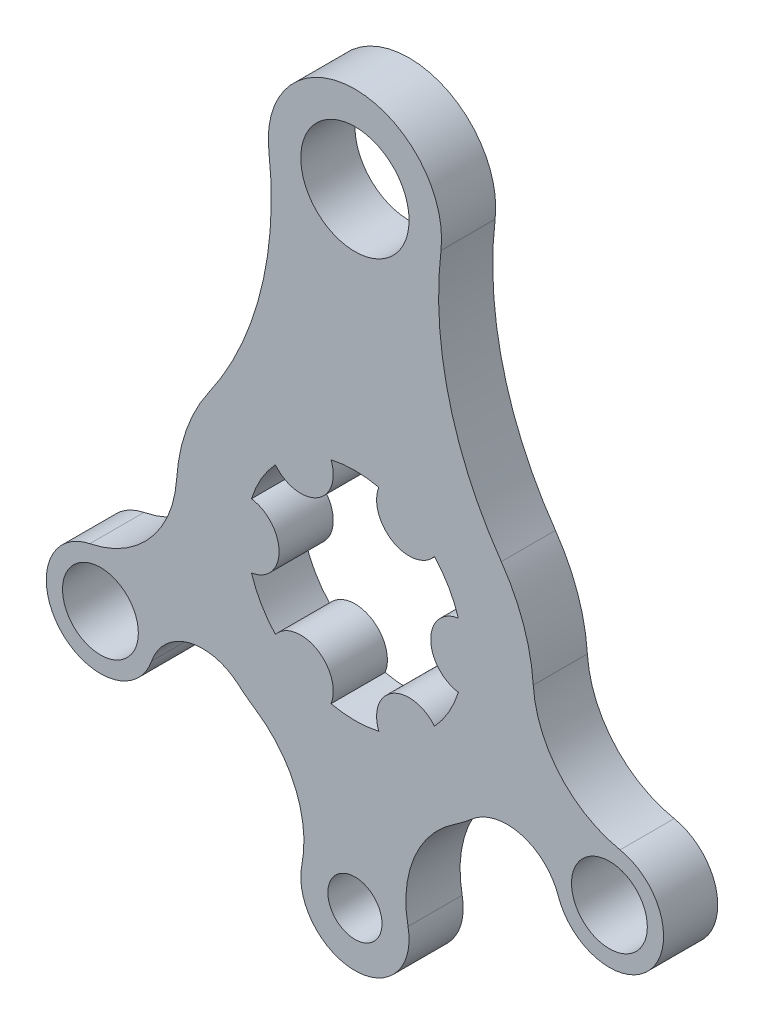
SolidWorks part; units mm, degrees
ref_plane "Front Plane" through (0, 0, 0) normal (0, 0, 1) x (1, 0, 0)
ref_plane "Top Plane" through (0, 0, 0) normal (0, 1, 0) x (1, 0, 0)
ref_plane "Right Plane" through (0, 0, 0) normal (1, 0, 0) x (0, 0, -1)
sketch "Sketch1" plane through (0, 0, 0) normal (0, 0, 1) x (1, 0, 0)
  line L0 (0, 0) -> (20560.2154, 0) construction
  line L1 (0, 0) -> (0, 20560.2154) construction
  arc A0 (4.4126, 19.5071) -> (-4.4126, 19.5071) centre (0, 0) ccw
  arc A1 (19.1, 5.9321) -> (19.1, -5.9321) centre (20, 0) ccw
  circle A2 centre (0, 65) radius 10
  arc A3 (15.8903, 63.1292) -> (-15.8903, 63.1292) centre (0, 65) ccw
  circle A4 centre (0, -50) radius 5
  arc A5 (-9.804, -48.03) -> (9.804, -48.03) centre (0, -50) ccw
  arc A6 (37.5509, -29.2733) -> (48.9633, -16.1946) centre (47, -26) ccw
  circle A7 centre (47, -26) radius 7
  arc A8 (14.6874, -13.575) -> (4.4126, -19.5071) centre (10, -17.3205) ccw
  arc A9 (-4.4126, -19.5071) -> (-14.6874, -13.575) centre (-10, -17.3205) ccw
  arc A10 (-19.1, -5.9321) -> (-19.1, 5.9321) centre (-20, 0) ccw
  arc A11 (-14.6874, 13.575) -> (-4.4126, 19.5071) centre (-10, 17.3205) ccw
  arc A12 (4.4126, 19.5071) -> (14.6874, 13.575) centre (10, 17.3205) ccw
  arc A13 (-14.6874, 13.575) -> (-19.1, 5.9321) centre (0, 0) ccw
  arc A14 (-19.1, -5.9321) -> (-14.6874, -13.575) centre (0, 0) ccw
  arc A15 (-4.4126, -19.5071) -> (4.4126, -19.5071) centre (0, 0) ccw
  arc A16 (14.6874, -13.575) -> (19.1, -5.9321) centre (0, 0) ccw
  arc A17 (19.1, 5.9321) -> (14.6874, 13.575) centre (0, 0) ccw
  arc A18 (-27.0298, 18.9312) -> (-33, 0) centre (0, 0) ccw
  arc A19 (32.9314, 2.127) -> (48.9633, -16.1946) centre (52.8898, 3.4162) ccw
  arc A20 (37.5509, -29.2733) -> (21.5665, -24.9777) centre (28.1018, -32.5467) ccw
  arc A21 (18.3132, -27.4523) -> (9.804, -48.03) centre (29.4121, -44.09) ccw
  arc A22 (15.8903, 63.1292) -> (27.0298, 18.9312) centre (79.4513, 55.6462) ccw
  circle A23 centre (-47, -26) radius 7
  arc A24 (-37.5509, -29.2733) -> (-48.9633, -16.1946) centre (-47, -26) cw
  arc A25 (-18.3132, -27.4523) -> (-9.804, -48.03) centre (-29.4121, -44.09) cw
  arc A26 (-37.5509, -29.2733) -> (-21.5665, -24.9777) centre (-28.1018, -32.5467) cw
  arc A27 (-32.9314, 2.127) -> (-48.9633, -16.1946) centre (-52.8898, 3.4162) cw
  arc A28 (-15.8903, 63.1292) -> (-27.0298, 18.9312) centre (-79.4513, 55.6462) cw
  arc A29 (33, 0) -> (27.0298, 18.9312) centre (0, 0) ccw
  arc A30 (18.3132, -27.4523) -> (21.5665, -24.9777) centre (0, 0) ccw
  arc A31 (-21.5665, -24.9777) -> (-18.3132, -27.4523) centre (0, 0) ccw
  point P30 (0, 0)
  dimension "D1" = 40
  dimension "D2" = 12
  dimension "D3" = 20
  dimension "D4" = 32
  dimension "D5" = 10
  dimension "D6" = 20
  dimension "D7" = 20
  dimension "D8" = 14
  dimension "D10" = 66
  dimension "D15" = 64
  dimension "D16" = 20
  dimension "D17" = 10
  dimension "D18" = 20
  dimension "D11" = 65
  dimension "D12" = 50
  dimension "D13" = 24
  dimension "D14" = 47
  dimension "D9" = 6
extrude "Boss-Extrude1" add sketch "Sketch1" along normal mid plane 10
